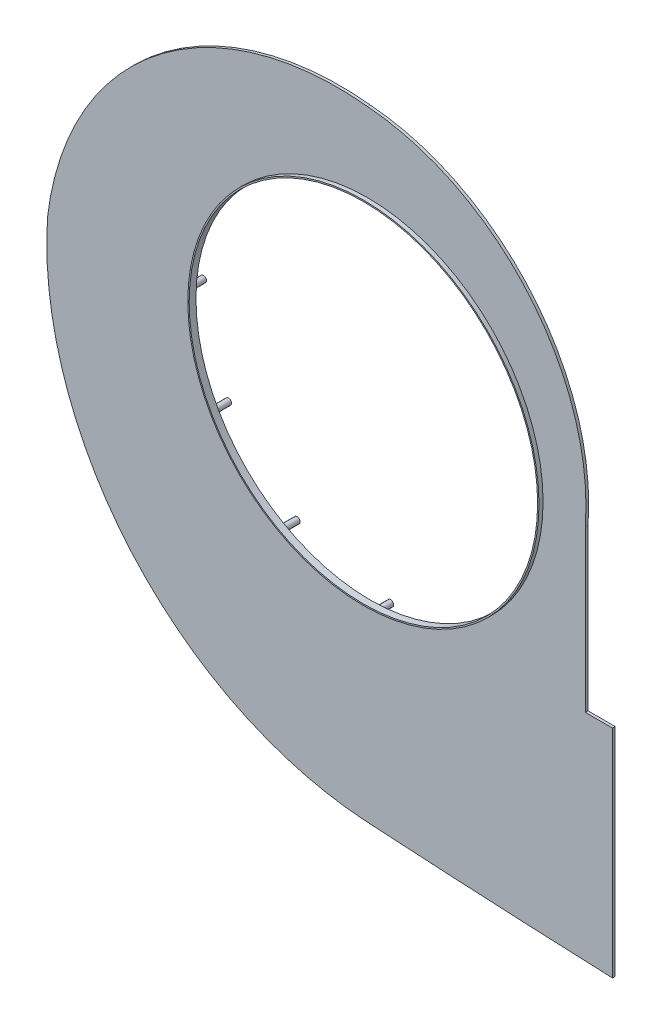
SolidWorks part; units mm, degrees
material "ASTM A36 Steel"
ref_plane "Front Plane" through (0, 0, 0) normal (0, 0, 1) x (1, 0, 0)
ref_plane "Top Plane" through (0, 0, 0) normal (0, 1, 0) x (1, 0, 0)
ref_plane "Right Plane" through (0, 0, 0) normal (1, 0, 0) x (0, 0, -1)
sketch "Sketch1" plane through (0, 0, 0) normal (0, 0, 1) x (1, 0, 0)
  line L0 (60.4241, 203.7442) -> (302.1207, 203.7442) construction
  line L1 (865.2691, 521.0572) -> (865.2691, 757.0572)
  line L2 (865.2691, 521.0572) -> (905.2691, 521.0572)
  line L3 (905.2691, 521.0572) -> (905.2691, 203.0572)
  line L4 (905.2691, 362.0572) -> (1163.8144, 362.0572) construction
  line L5 (1052.4058, 757.0572) -> (545.2691, 757.0572) construction
  line L6 (545.2691, 757.0572) -> (545.2691, 1175.6872) construction
  arc A1 (75.2691, 757.0572) -> (545.2691, 1132.0572) centre (500.9272, 705.599) cw
  arc A2 (545.2691, 221.2717) -> (75.2691, 757.0572) centre (576.0662, 722.3261) cw
  arc A3 (545.2691, 1132.0572) -> (865.2691, 757.0572) centre (517.3547, 784.2035) cw
  arc A4 (545.2691, 221.2717) -> (905.2691, 203.0572) centre (1565.8135, 16825.0409) ccw
  dimension "D1" = 40
  dimension "D9" = 502
  dimension "D2" = 320
  dimension "D3" = 470
  dimension "D4" = 375
  dimension "D5" = 395
  dimension "D6" = 318
extrude "Boss-Extrude1" add sketch "Sketch1" along normal blind 4
sketch "Sketch2" plane through (0, 0, 4) normal (0, 0, 1) x (1, 0, 0)
  line L0 (865.2691, 521.0572) -> (865.2691, 757.0572) construction
  circle A0 centre (545.2691, 758.0572) radius 256
  dimension "D1" = 512
  dimension "D2" = 374
  dimension "D3" = 320
extrude "Cut-Extrude1" cut sketch "Sketch2" against normal blind 50
sketch "Sketch3" plane through (0, 0, 0) normal (0, 0, -1) x (-1, 0, 0)
  circle A0 centre (-545.2691, 758.0572) radius 256
extrude "Extrude-Thin1" add sketch "Sketch3" against normal blind 10 thin
sketch "Sketch4" plane through (0, 0, 0) normal (0, 0, -1) x (-1, 0, 0)
  line L0 (-545.2691, 1033.0572) -> (-545.2691, 758.0572) construction
  circle A0 centre (-545.2691, 1033.0572) radius 4.5
  circle A1 centre (-545.2691, 758.0572) radius 256 construction
  point P4 (-545.2691, 758.0572)
  dimension "D1" = 9
  dimension "D2" = 275
extrude "Boss-Extrude2" add sketch "Sketch4" along normal blind 30
pattern_circular "CirPattern1" count 12 every 30 about axis through (545.2691, 758.0572, 0) along (0, 0, 1) of "Boss-Extrude2"
